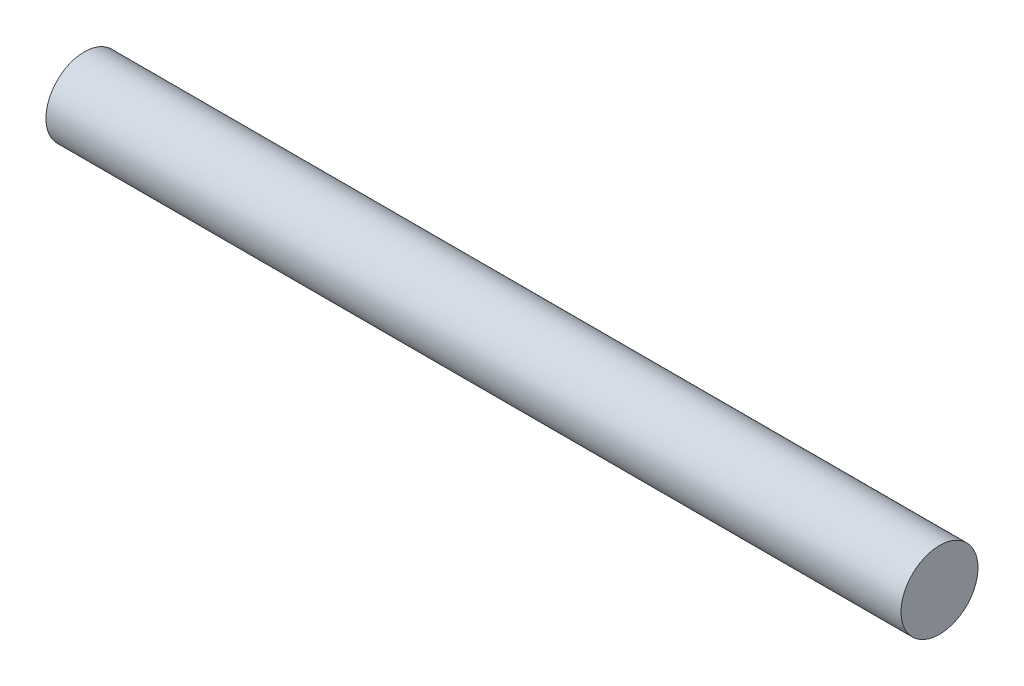
SolidWorks part; units mm, degrees
material "Stainless Steel (ferritic)"
ref_plane "Front Plane" through (0, 0, 0) normal (0, 0, 1) x (1, 0, 0)
ref_plane "Top Plane" through (0, 0, 0) normal (0, 1, 0) x (1, 0, 0)
ref_plane "Right Plane" through (0, 0, 0) normal (1, 0, 0) x (0, 0, -1)
sketch "Sketch1" plane through (0, 0, 0) normal (1, 0, 0) x (0, 0, -1)
  circle A0 centre (0, 0) radius 45
extrude "Boss-Extrude1" add sketch "Sketch1" along normal blind 1000
